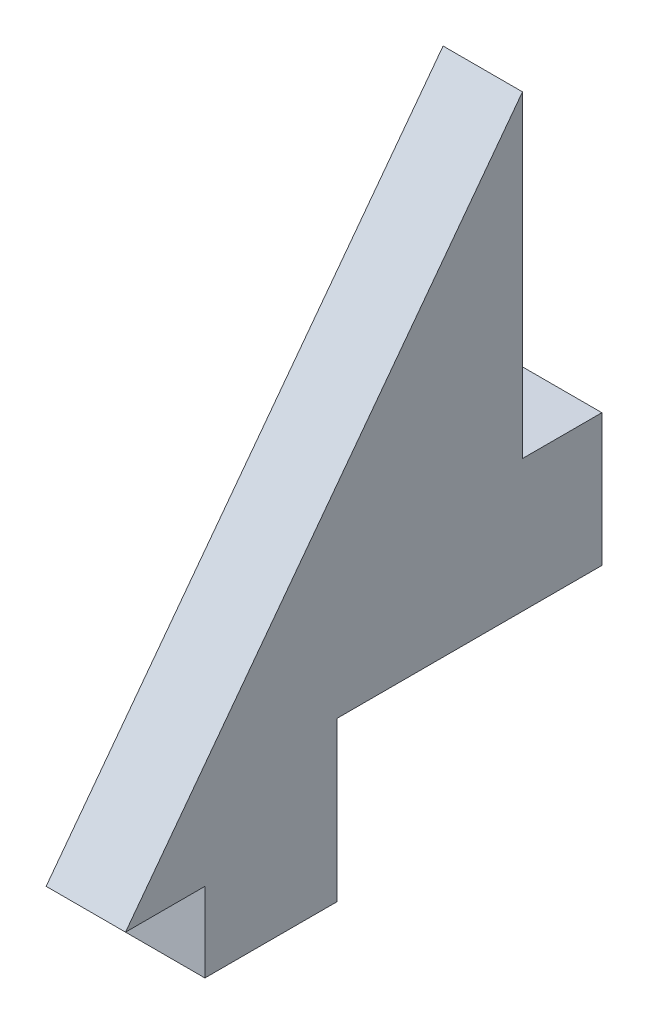
SolidWorks part; units mm, degrees
ref_plane "Front Plane" through (0, 0, 0) normal (0, 0, 1) x (1, 0, 0)
ref_plane "Top Plane" through (0, 0, 0) normal (0, 1, 0) x (1, 0, 0)
ref_plane "Right Plane" through (0, 0, 0) normal (1, 0, 0) x (0, 0, -1)
sketch "Sketch1" plane through (0, 0, 0) normal (1, 0, 0) x (0, 0, -1)
  line L0 (0, 20) -> (-15, 0)
  line L1 (-15, 0) -> (-12, 0)
  line L2 (0, 0) -> (0, 3)
  line L3 (-7, 0) -> (0, 0)
  line L5 (-12, 0) -> (-12, -3)
  line L6 (-12, -3) -> (-7, -3)
  line L7 (-7, 0) -> (-7, -3)
  line L8 (0, 3) -> (3, 3)
  line L10 (0, 8) -> (3, 8)
  line L11 (3, 3) -> (3, 8)
  line L12 (0, 8) -> (0, 20)
  dimension "D1" = 15
  dimension "D2" = 20
  dimension "D3" = 3
  dimension "D4" = 5
  dimension "D5" = 5
  dimension "D6" = 3
  dimension "D7" = 7
  dimension "D8" = 3
extrude "Boss-Extrude1" add sketch "Sketch1" along normal blind 3
sketch "Sketch2" plane through (3, 0, 0) normal (1, 0, 0) x (0, 0, -1)
  line L0 (-7, -3) -> (-7, 0) construction
  line L1 (0, 0) -> (-7, 0)
  line L2 (0, 0) -> (0, 3)
  line L3 (0, 3) -> (-7, 3)
  line L4 (-7, 0) -> (-7, 3)
  line L5 (0, 3) -> (3, 3) construction
extrude "Cut-Extrude1" cut sketch "Sketch2" against normal blind 10
